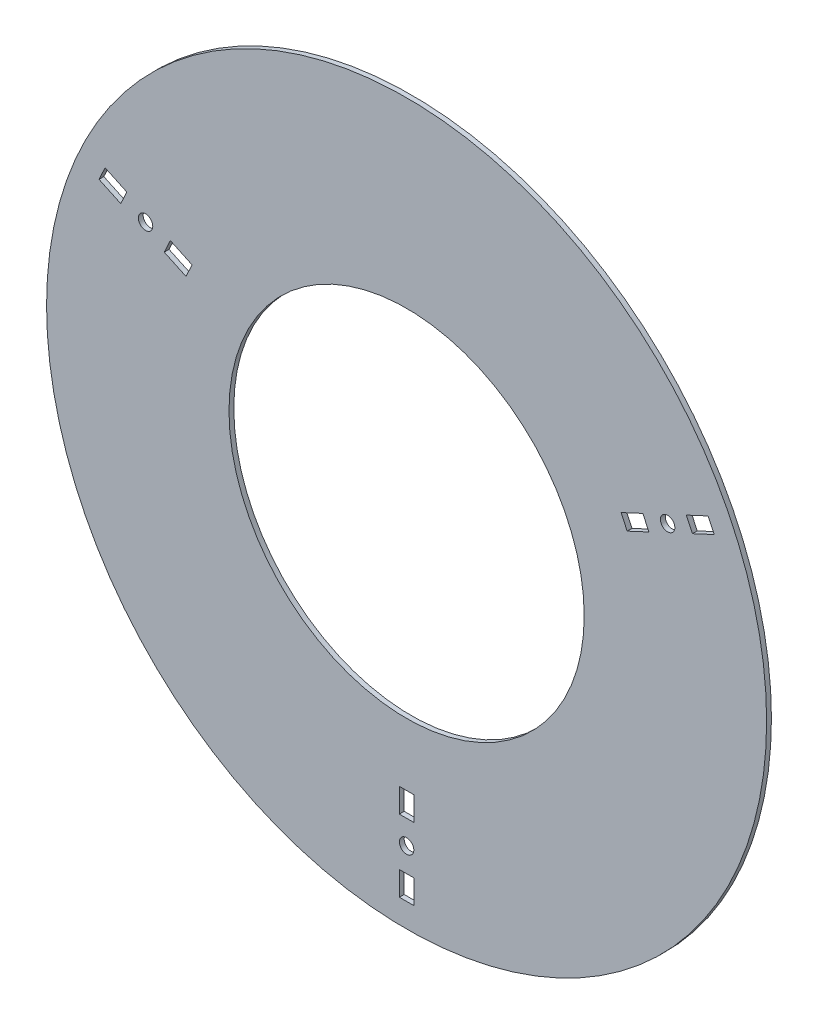
SolidWorks part; units mm, degrees
ref_plane "Front Plane" through (0, 0, 0) normal (0, 0, 1) x (1, 0, 0)
ref_plane "Top Plane" through (0, 0, 0) normal (0, 1, 0) x (1, 0, 0)
ref_plane "Right Plane" through (0, 0, 0) normal (1, 0, 0) x (0, 0, -1)
sketch "Sketch1" plane through (0, 0, 0) normal (0, 0, 1) x (1, 0, 0)
  line L0 (0, 0) -> (0, -75) construction
  line L1 (0, 0) -> (67.9731, 31.6964) construction
  line L2 (0, 0) -> (-67.9731, 31.6964) construction
  circle A0 centre (0, 0) radius 37
  circle A1 centre (0, 0) radius 75
  circle A2 centre (0, 0) radius 60 construction
  point P8 (54.3785, 25.3571)
  point P9 (-54.3785, 25.3571)
  point P10 (0, -60)
  line B0 (0, -55) -> (0, -65) construction
  line B1 (1.5, -55) -> (1.5, -50)
  line B2 (1.5, -55) -> (-1.5, -55)
  line B3 (-1.5, -55) -> (-1.5, -50)
  line B4 (1.5, -50) -> (-1.5, -50)
  line B5 (1.5, -65) -> (1.5, -70)
  line B6 (1.5, -65) -> (-1.5, -65)
  line B7 (-1.5, -65) -> (-1.5, -70)
  line B8 (1.5, -70) -> (-1.5, -70)
  circle B9 centre (0, -60) radius 1.5
  line B10 (49.8469, 23.244) -> (58.91, 27.4702) construction
  line B11 (49.213, 24.6035) -> (44.6815, 22.4904)
  line B12 (49.213, 24.6035) -> (50.4809, 21.8845)
  line B13 (50.4809, 21.8845) -> (45.9493, 19.7715)
  line B14 (44.6815, 22.4904) -> (45.9493, 19.7715)
  line B15 (58.2761, 28.8296) -> (62.8076, 30.9427)
  line B16 (58.2761, 28.8296) -> (59.5439, 26.1107)
  line B17 (59.5439, 26.1107) -> (64.0755, 28.2238)
  line B18 (62.8076, 30.9427) -> (64.0755, 28.2238)
  circle B19 centre (54.3785, 25.3571) radius 1.5
  line B20 (-58.91, 27.4702) -> (-49.8469, 23.244) construction
  line B21 (-58.2761, 28.8296) -> (-62.8076, 30.9427)
  line B22 (-58.2761, 28.8296) -> (-59.5439, 26.1107)
  line B23 (-59.5439, 26.1107) -> (-64.0755, 28.2238)
  line B24 (-62.8076, 30.9427) -> (-64.0755, 28.2238)
  line B25 (-49.213, 24.6035) -> (-44.6815, 22.4904)
  line B26 (-49.213, 24.6035) -> (-50.4809, 21.8845)
  line B27 (-50.4809, 21.8845) -> (-45.9493, 19.7715)
  line B28 (-44.6815, 22.4904) -> (-45.9493, 19.7715)
  circle B29 centre (-54.3785, 25.3571) radius 1.5
  dimension "D1" = 74
  dimension "D2" = 150
  dimension "D4" = 120
  dimension "D3" = 115
sketch_block_instance "Trou M3 plots 3mm-1"
sketch_block "Trou M3 plots 3mm" parameters "D2"=3, "D1"=3, "D3"=5, "D4"=10
sketch_block_instance "Trou M3 plots 3mm-2"
sketch_block_instance "Trou M3 plots 3mm-3"
extrude "Boss-Extrude1" add sketch "Sketch1" along normal blind 1
